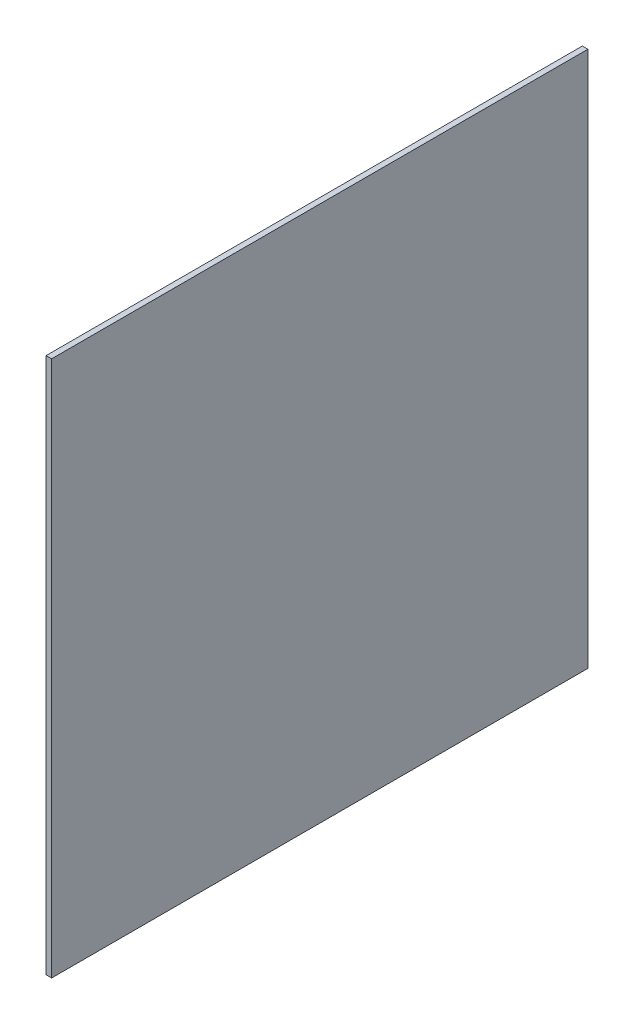
SolidWorks part; units mm, degrees
ref_plane "前视基准面" through (0, 0, 0) normal (0, 0, 1) x (1, 0, 0)
ref_plane "上视基准面" through (0, 0, 0) normal (0, 1, 0) x (1, 0, 0)
ref_plane "右视基准面" through (0, 0, 0) normal (1, 0, 0) x (0, 0, -1)
other "Configuration Table"
sketch "草图2" plane through (0, 0, 0) normal (1, 0, 0) x (0, 0, -1)
  line L1 (-58.0652, 50.6863) -> (231.9348, 50.6863)
  line L2 (-58.0652, 50.6863) -> (-58.0652, -239.3137)
  line L3 (-58.0652, -239.3137) -> (231.9348, -239.3137)
  line L4 (231.9348, 50.6863) -> (231.9348, -239.3137)
  dimension "D1" = 290
  dimension "D2" = 290
extrude "凸台-拉伸1" add sketch "草图2" along normal blind 3
